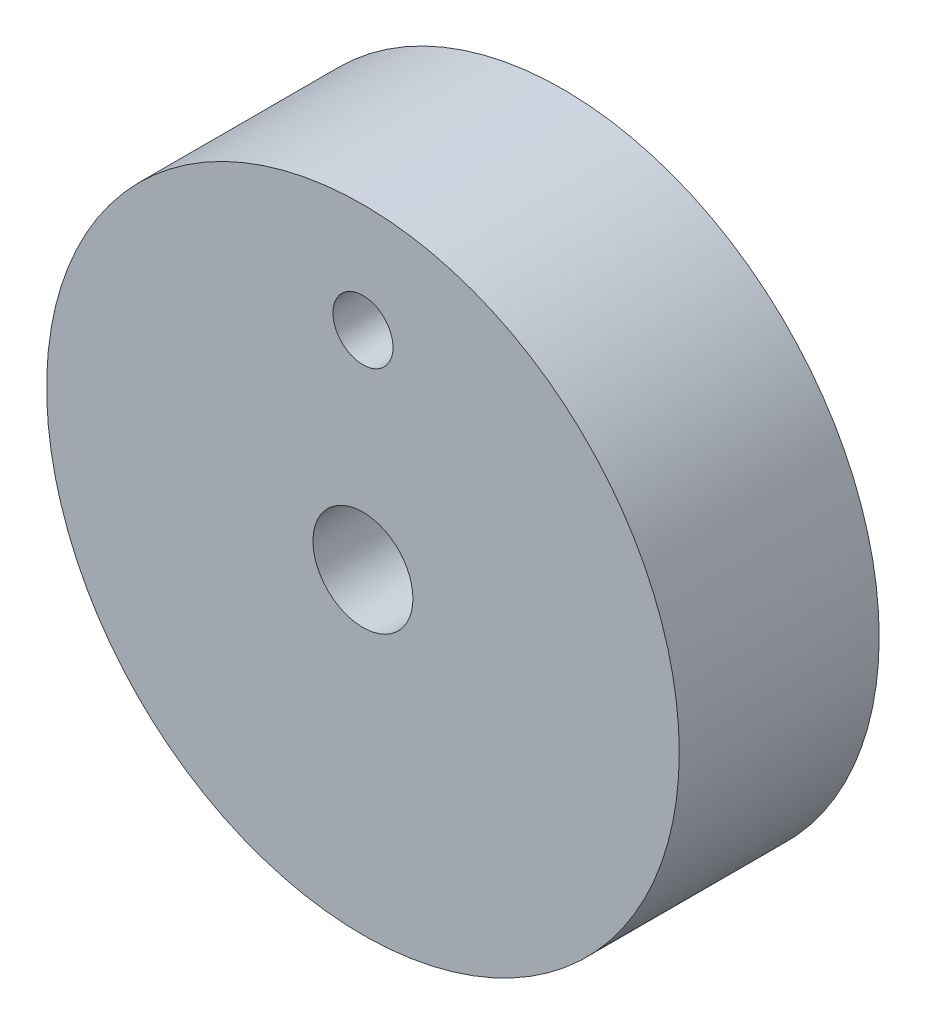
SolidWorks part; units mm, degrees
ref_plane "Front Plane" through (0, 0, 0) normal (0, 0, 1) x (1, 0, 0)
ref_plane "Top Plane" through (0, 0, 0) normal (0, 1, 0) x (1, 0, 0)
ref_plane "Right Plane" through (0, 0, 0) normal (1, 0, 0) x (0, 0, -1)
sketch "Sketch1" plane through (0, 0, 0) normal (0, 0, 1) x (1, 0, 0)
  circle A0 centre (0, 0) radius 317.5
  circle A1 centre (0, 0) radius 50.165
  dimension "D1" = 635
  dimension "D2" = 100.33
extrude "Boss-Extrude1" add sketch "Sketch1" along normal blind 200.66
sketch "Sketch2" plane through (0, 0, 200.66) normal (0, 0, 1) x (1, 0, 0)
  circle A0 centre (0, 208.3386) radius 30.1255
extrude "Cut-Extrude1" cut sketch "Sketch2" against normal blind 254
